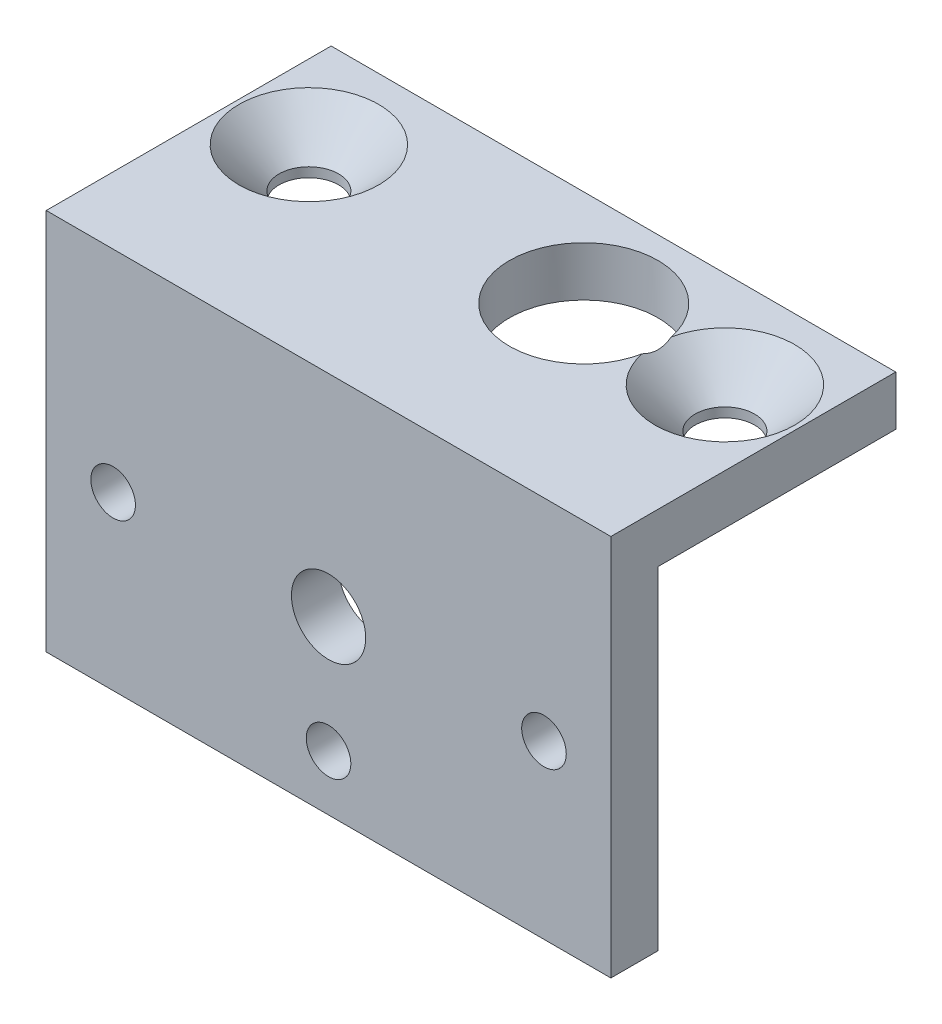
SolidWorks part; units mm, degrees
ref_plane "Front Plane" through (0, 0, 0) normal (0, 0, 1) x (1, 0, 0)
ref_plane "Top Plane" through (0, 0, 0) normal (0, 1, 0) x (1, 0, 0)
ref_plane "Right Plane" through (0, 0, 0) normal (1, 0, 0) x (0, 0, -1)
sketch "Sketch1" plane through (0, 0, 0) normal (0, 0, 1) x (1, 0, 0)
  line L0 (0, 0) -> (0, -1.3073) construction
  line L1 (-19.0018, 12.8677) -> (19.0018, 12.8677)
  line L2 (-19.0018, 12.8677) -> (-19.0018, -12.8677)
  line L3 (-19.0018, -12.8677) -> (19.0018, -12.8677)
  line L4 (19.0018, 12.8677) -> (19.0018, -12.8677)
  line L5 (-19.0018, 12.8677) -> (19.0018, -12.8677) construction
  line L6 (-19.0018, -12.8677) -> (19.0018, 12.8677) construction
  circle A1 centre (-14.5, -1.3073) radius 1.5
  circle A2 centre (14.5, -1.3073) radius 1.5
  circle A3 centre (0, -1.3073) radius 2.5
  circle A4 centre (0, -9.1323) radius 1.5
  point P0 (0, 0)
  dimension "D1" = 14.5
  dimension "D3" = 14.175
  dimension "D4" = 22
  dimension "D2" = 14.5
extrude "Boss-Extrude1" add sketch "Sketch1" along normal blind 3.175
sketch "Sketch2" plane through (0, 0, 0) normal (0, 0, -1) x (-1, 0, 0)
  line L0 (-19.0018, -12.8677) -> (-19.0018, 12.8677) construction
  line L1 (19.0018, 12.8677) -> (-19.0018, 12.8677)
  line L2 (19.0018, 12.8677) -> (19.0018, 9.525)
  line L3 (19.0018, 9.525) -> (-19.0018, 9.525)
  line L4 (-19.0018, 12.8677) -> (-19.0018, 9.525)
extrude "Boss-Extrude2" add sketch "Sketch2" along normal blind 16
sketch "Sketch3" plane through (0, 9.525, 0) normal (0, -1, 0) x (1, 0, 0)
  line L0 (-19.0018, 0) -> (19.0018, 0) construction
  line L1 (14, -9.5) -> (-14, -9.5) construction
  circle A0 centre (4.5, -9.5) radius 5
  circle A1 centre (-14, -9.5) radius 2
  circle A2 centre (14, -9.5) radius 2
  dimension "D1" = 9.5
  dimension "D2" = 28
  dimension "D3" = 9.5
extrude "Cut-Extrude1" cut sketch "Sketch3" against normal blind 10
hole_wizard "Escareado para parafuso de máquina com cabeça chata de M42" positions "Esboço4" profile "Esboço3" countersink size "M4" standard "Métrico Ansi" end condition through all
sketch "Esboço4" plane through (0, 12.8677, 0) normal (0, 1, 0) x (-1, 0, 0)
  point P0 (14, -9.5)
  point P4 (-14, -9.5)
sketch "Esboço3" plane through (-14, 12.8677, -9.5) normal (1, 0, 0) x (0, 0, 1)
  line L0 (0, 0) -> (0, 25.7354)
  line L1 (0, 25.7354) -> (2, 25.7354)
  line L2 (2, 25.7354) -> (2, 2.7)
  line L3 (2, 2.7) -> (4.7, 0)
  line L5 (4.7, 0) -> (0, 0)
  line L6 (-2, 2.7) -> (-4.7, 0) construction
  line L11 (0, -6.35) -> (0, 107.95) construction
  dimension "Thru Hole Dia." = 4
  dimension "Thru Hole Depth" = 25.7354
  dimension "Near C'Sink Dia." = 9.4
  dimension "Near C'Sink Angle" = 90
